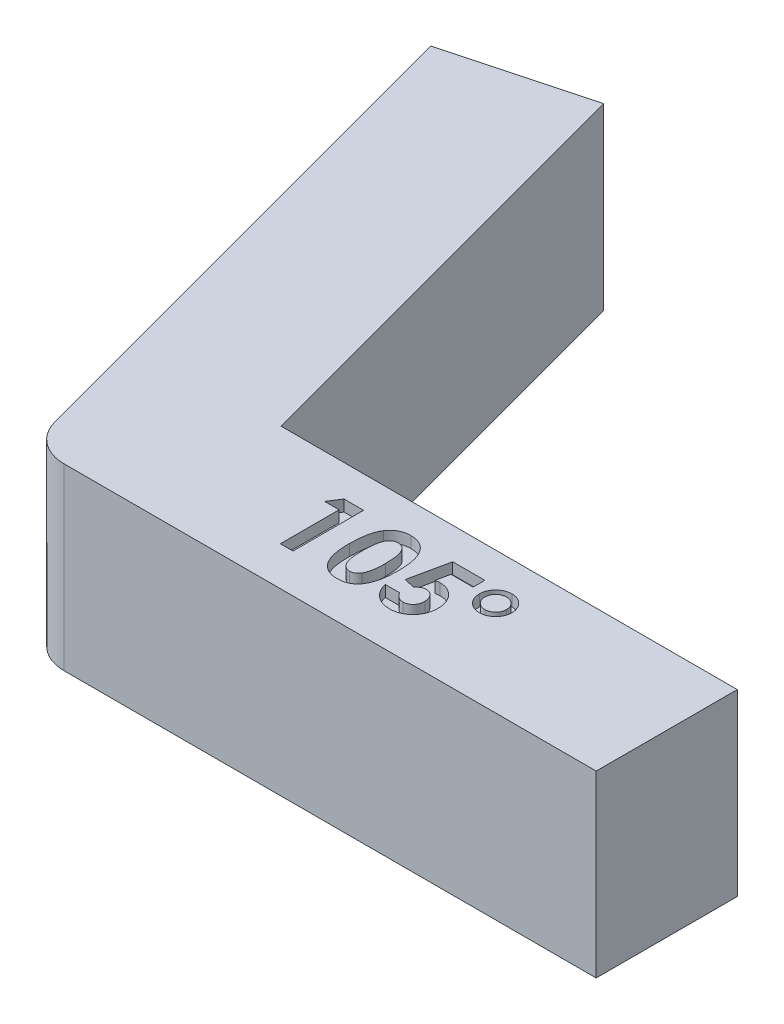
SolidWorks part; units mm, degrees
ref_plane "Front Plane" through (0, 0, 0) normal (0, 0, 1) x (1, 0, 0)
ref_plane "Top Plane" through (0, 0, 0) normal (0, 1, 0) x (1, 0, 0)
ref_plane "Right Plane" through (0, 0, 0) normal (1, 0, 0) x (0, 0, -1)
sketch "Sketch1" plane through (0, 0, 0) normal (0, 1, 0) x (1, 0, 0)
  line L0 (0, 0) -> (-10.3528, 38.637)
  line L1 (0, 0) -> (40, 0)
  line L2 (7.6733, 10) -> (40, 10)
  line L3 (7.6733, 10) -> (-0.6935, 41.2252)
  line L4 (-10.3528, 38.637) -> (-0.6935, 41.2252)
  line L5 (40, 10) -> (40, 0)
  dimension "D1" = 105
  dimension "D2" = 40
  dimension "D3" = 10
extrude "Boss-Extrude1" add sketch "Sketch1" along normal blind 12.7
sketch "Sketch2" plane through (0, 12.7, 0) normal (0, 1, 0) x (1, 0, 0)
  text T0 "<b>105°</b>" font "Century Gothic" height 5
extrude "Cut-Extrude1" cut sketch "Sketch2" against normal blind 0.8
fillet "Fillet1" radius 3 1 edges at (0, 6.35, 0)
